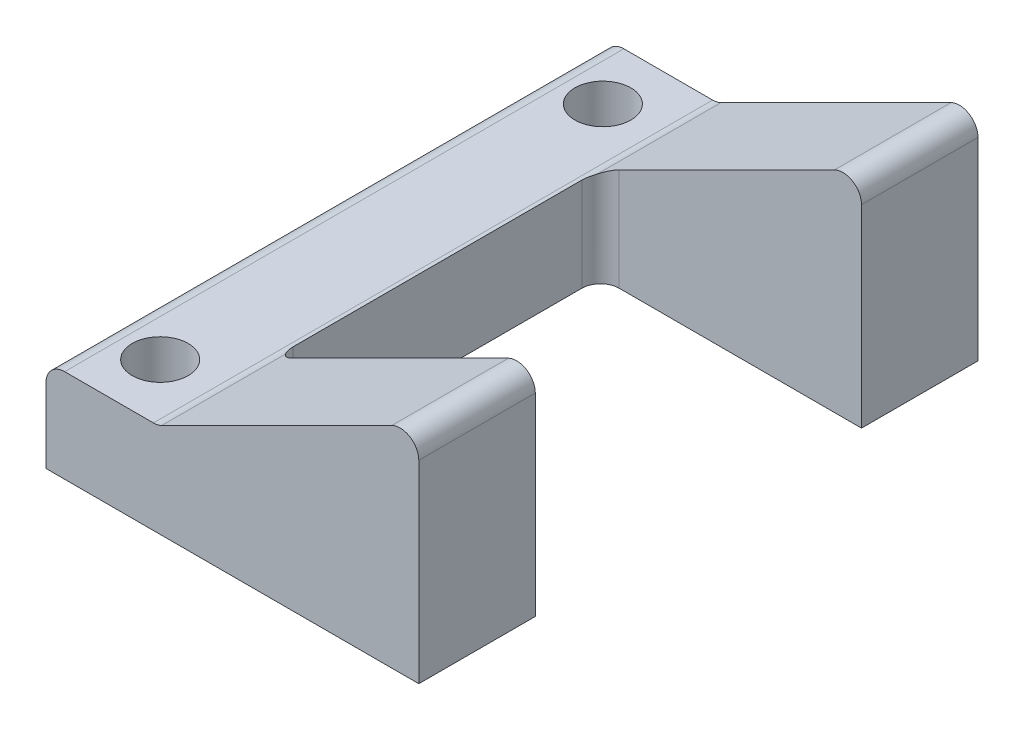
SolidWorks part; units mm, degrees
ref_plane "前视基准面" through (0, 0, 0) normal (0, 0, 1) x (1, 0, 0)
ref_plane "上视基准面" through (0, 0, 0) normal (0, 1, 0) x (1, 0, 0)
ref_plane "右视基准面" through (0, 0, 0) normal (1, 0, 0) x (0, 0, -1)
sketch "Sketch1" plane through (0, 0, 0) normal (0, 0, 1) x (1, 0, 0)
  line L0 (0, 0) -> (0, 4)
  line L2 (20, 10.382) -> (20, 0)
  line L3 (20, 0) -> (0, 0)
  line L4 (1, 5) -> (5.7639, 5)
  line L5 (6.2111, 5.1056) -> (18.5528, 11.2764)
  arc A1 (0, 4) -> (1, 5) centre (1, 4) cw
  arc A2 (5.7639, 5) -> (6.2111, 5.1056) centre (5.7639, 6) ccw
  arc A3 (18.5528, 11.2764) -> (20, 10.382) centre (19, 10.382) cw
  point P4 (20, 0)
  point P7 (20, 0)
  point P11 (0, 5)
  point P14 (6, 5)
  point P17 (20, 12)
  point P18 (0, 0)
  point P19 (19.9377, 0)
  dimension "D1" = 5
  dimension "D2" = 6
  dimension "D3" = 12
  dimension "D4" = 20
extrude "Boss-Extrude1" add sketch "Sketch1" along normal mid plane 30
sketch "Sketch2" plane through (0, 0, 0) normal (0, -1, 0) x (1, 0, 0)
  line L1 (0, 15) -> (0, -15) construction
  line L3 (27.5831, 0) -> (-6.4229, 0) construction
  line L6 (20, -8.75) -> (20, 8.75)
  line L7 (20, 15) -> (20, -15) construction
  line L8 (20, 8.75) -> (7, 8.75)
  line L9 (6, 7.75) -> (6, -7.75)
  line L10 (20, -8.75) -> (7, -8.75)
  arc A0 (7, -8.75) -> (6, -7.75) centre (7, -7.75) cw
  arc A1 (7, 8.75) -> (6, 7.75) centre (7, 7.75) ccw
  circle A2 centre (3, 11.875) radius 1.5
  circle A3 centre (3, -11.875) radius 1.5
  point P10 (0, 0)
  point P11 (14.4787, 0)
  point P14 (6, 0)
  point P15 (20, 0)
  point P17 (6, -8.75)
  point P20 (6, 8.75)
  point P25 (3, -11.3852)
  dimension "D3" = 1
  dimension "D4" = 3
  dimension "D1" = 17.5
  dimension "D2" = 6
  dimension "D5" = 3
  dimension "D6" = 23.75
extrude "Cut-Extrude1" cut sketch "Sketch2" against normal blind 30
